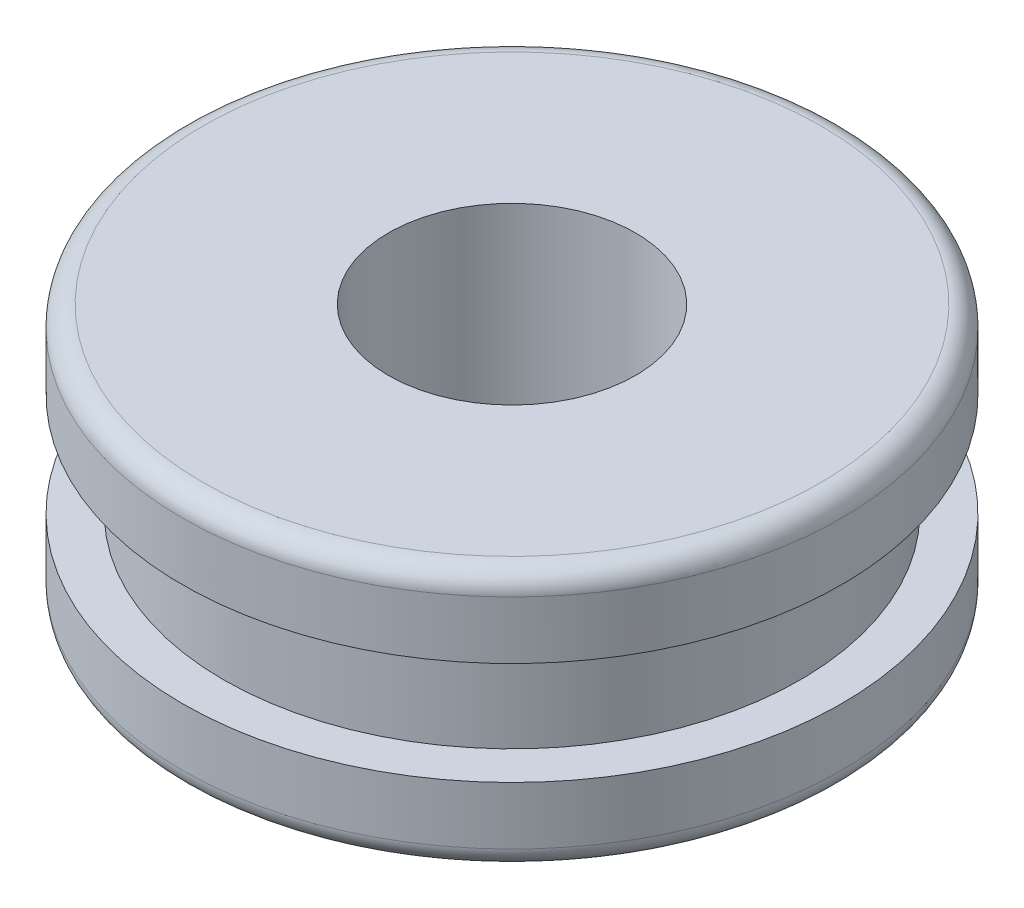
SolidWorks part; units mm, degrees
ref_plane "Alzado" through (0, 0, 0) normal (0, 0, 1) x (1, 0, 0)
ref_plane "Planta" through (0, 0, 0) normal (0, 1, 0) x (1, 0, 0)
ref_plane "Vista lateral" through (0, 0, 0) normal (1, 0, 0) x (0, 0, -1)
sketch "Croquis base" plane through (0, 0, 0) normal (0, 1, 0) x (1, 0, 0)
  circle A0 centre (0, 0) radius 3.5
  dimension "D1" = 7
extrude "Saliente-Extruir3" add sketch "Croquis base" along normal blind 1.25
ref_plane "Symmetry plain" through (0, 0.625, 0) normal (0, 1, 0) x (1, 0, 0)
sketch "Croquis cap" plane through (0, 1.25, 0) normal (0, 1, 0) x (1, 0, 0)
  circle A0 centre (0, 0) radius 4
  dimension "D1" = 8
extrude "Saliente-Extruir4" add sketch "Croquis cap" along normal blind 0.95
fillet "Redondeo1" radius 0.25 1 edges at (0, 2.2, 4)
mirror "Simetría1" about plane through (0, 0.625, 0) normal (0, 1, 0) of "Redondeo1", "Saliente-Extruir4"
sketch "Croquis barreno" plane through (0, 2.2, 0) normal (0, 1, 0) x (1, 0, 0)
  circle A0 centre (0, 0) radius 1.5
  dimension "D1" = 3
extrude "Cortar-Extruir1" cut sketch "Croquis barreno" against normal through all
